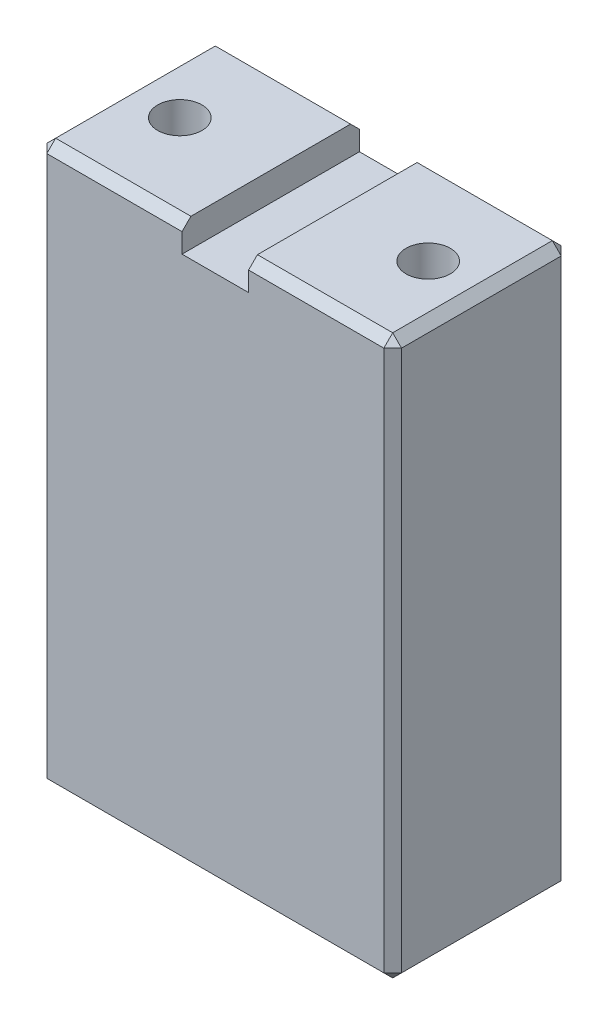
SolidWorks part; units mm, degrees
material "Plain Carbon Steel"
ref_plane "Front Plane" through (0, 0, 0) normal (0, 0, 1) x (1, 0, 0)
ref_plane "Top Plane" through (0, 0, 0) normal (0, 1, 0) x (1, 0, 0)
ref_plane "Right Plane" through (0, 0, 0) normal (1, 0, 0) x (0, 0, -1)
sketch "Sketch1" plane through (0, 0, 0) normal (0, 0, 1) x (1, 0, 0)
  line L1 (-20, -31.5) -> (20, -31.5)
  line L2 (-20, -31.5) -> (-20, 31.5)
  line L3 (-20, 31.5) -> (20, 31.5)
  line L4 (20, -31.5) -> (20, 31.5)
  line L5 (-20, -31.5) -> (20, 31.5) construction
  line L6 (-20, 31.5) -> (20, -31.5) construction
  point P0 (0, 0)
  dimension "D1" = 40
  dimension "D2" = 63
extrude "Boss-Extrude1" add sketch "Sketch1" along normal blind 20
sketch "Sketch2" plane through (0, 31.5, 0) normal (0, 1, 0) x (1, 0, 0)
  line L0 (20, 0) -> (-20, 0) construction
  line L1 (-3.75, 0) -> (3.75, 0)
  line L2 (-3.75, 0) -> (-3.75, -20)
  line L3 (-3.75, -20) -> (3.75, -20)
  line L4 (3.75, 0) -> (3.75, -20)
  line L5 (20, -20) -> (-20, -20) construction
  line L6 (0, 0) -> (0, -20) construction
  dimension "D1" = 7.5
extrude "Cut-Extrude1" cut sketch "Sketch2" against normal blind 3.2
hole_wizard "M8 Tapped Hole1" positions "Sketch5" profile "Sketch4" tap size "M8" standard "ISO"
sketch "Sketch5" plane through (0, -31.5, 0) normal (0, -1, 0) x (-1, 0, 0)
  line L0 (-20, -10) -> (20, -10) construction
  line L1 (-20, -20) -> (-20, 0) construction
  line L2 (20, -20) -> (20, 0) construction
  point P0 (-12, -10)
  point P2 (12, -10)
  point P13 (0, 0)
  point P14 (0, 0)
  dimension "D1" = 8
  dimension "D2" = 8
sketch "Sketch4" plane through (12, -31.5, 10) normal (1, 0, 0) x (0, 0, -1)
  line L0 (0, 0) -> (0, 21.7929)
  line L1 (0, 21.7929) -> (3.4, 19.75)
  line L2 (3.4, 19.75) -> (3.4, 0)
  line L5 (3.4, 0) -> (0, 0)
  line L10 (0, 21.7929) -> (-3.4, 19.75) construction
  line L11 (0, -6.35) -> (0, 107.95) construction
  dimension "Tap Drill Dia." = 6.8
  dimension "Tap Drill Depth" = 19.75
  dimension "Drill Angle" = 118
cosmetic thread "Hole Thread1" parameters "D1"=16, "D2"=8
cosmetic thread "Hole Thread2" parameters "D1"=16, "D2"=8
hole_wizard "M6 Tapped Hole1" positions "Sketch8" profile "Sketch7" tap size "M6" standard "ISO"
sketch "Sketch8" plane through (0, 31.5, 0) normal (0, 1, 0) x (1, 0, 0)
  line L0 (-20, -10) -> (20, -10) construction
  line L1 (-20, -20) -> (-20, 0) construction
  line L2 (20, -20) -> (20, 0) construction
  point P0 (-14, -10)
  point P2 (14, -10)
  point P13 (0, 0)
  point P14 (0, 0)
  dimension "D1" = 6
  dimension "D2" = 6
sketch "Sketch7" plane through (-14, 31.5, 10) normal (1, 0, 0) x (0, 0, 1)
  line L0 (0, 0) -> (0, 16.5022)
  line L1 (0, 16.5022) -> (2.5, 15)
  line L2 (2.5, 15) -> (2.5, 0)
  line L5 (2.5, 0) -> (0, 0)
  line L10 (0, 16.5022) -> (-2.5, 15) construction
  line L11 (0, -6.35) -> (0, 107.95) construction
  dimension "Tap Drill Dia." = 5
  dimension "Tap Drill Depth" = 15
  dimension "Drill Angle" = 118
cosmetic thread "Hole Thread3" parameters "D1"=12, "D2"=6
cosmetic thread "Hole Thread4" parameters "D1"=12, "D2"=6
chamfer "Chamfer1" distance 1 angle 45 14 edges at (-20, -31.5, 10) (-20, 0, 0) (0, -31.5, 0) (20, -31.5, 10) (-11.875, 31.5, 0) (-20, 31.5, 10) (-11.875, 31.5, 20) (-20, 0, 20) (0, -31.5, 20) (11.875, 31.5, 20) (11.875, 31.5, 0) (20, 0, 0) (20, 31.5, 10) (20, 0, 20)
